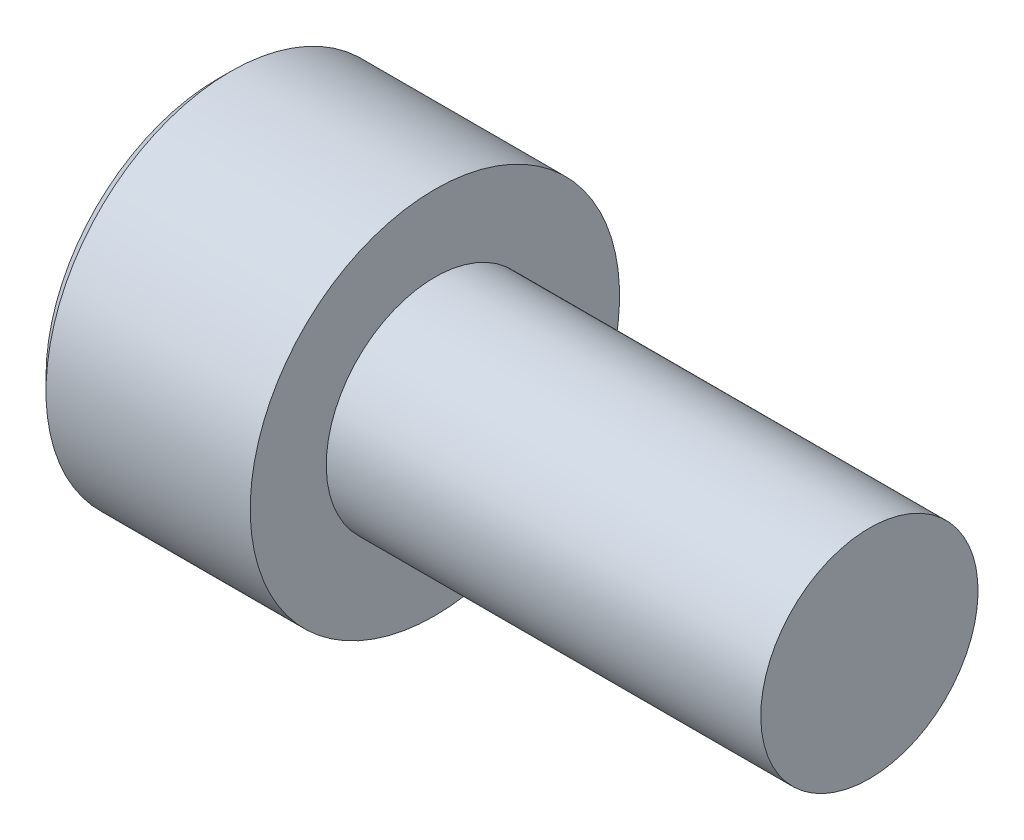
SolidWorks part; units mm, degrees
ref_plane "Front Plane" through (0, 0, 0) normal (0, 0, 1) x (1, 0, 0)
ref_plane "Top Plane" through (0, 0, 0) normal (0, 1, 0) x (1, 0, 0)
ref_plane "Right Plane" through (0, 0, 0) normal (1, 0, 0) x (0, 0, -1)
sketch "Sketch1" plane through (0, 0, 0) normal (0, 0, 1) x (1, 0, 0)
  line L0 (0, 2.5) -> (0, 4.25)
  line L1 (0, 4.25) -> (-5, 4.25)
  line L2 (-5, 4.25) -> (-5, 0)
  line L3 (-5, 0) -> (10, 0)
  line L4 (10, 0) -> (10, 2.5)
  line L5 (10, 2.5) -> (0, 2.5)
  line L6 (-5, 0) -> (10, 0) construction
  dimension "FIX_3" = 5
  dimension "FIX_4" = 8.5
  dimension "FIX_1" = 10
  dimension "FIX_2" = 5
revolve "Revolve1" add sketch "Sketch1" angle 360 about L6
cosmetic thread "Thread1" parameters "NFIX_1"=4.134
sketch "Sketch2" plane through (0, 0, 0) normal (0, 0, 1) x (1, 0, 0)
  line L0 (-5, 0) -> (-1.8453, 0)
  line L1 (-1.8453, 0) -> (-3, 2)
  line L2 (-3, 2) -> (-5, 2)
  line L3 (-5, 2) -> (-5, 0)
  line L4 (0, 0) -> (-5, 0) construction
  line L5 (-5, 0) -> (10, 0) construction
  dimension "FIX_8" = 4
  dimension "FIX_6" = 60
  dimension "FIX_7" = 2
revolve "Cut-Revolve1" cut sketch "Sketch2" angle 360 about L4
sketch "Sketch3" plane through (-5, 0, 0) normal (-1, 0, 0) x (0, 0, 1)
  line L1 (2.3094, 0) -> (1.1547, 2)
  line L2 (1.1547, 2) -> (-1.1547, 2)
  line L3 (-1.1547, 2) -> (-2.3094, 0)
  line L4 (-2.3094, 0) -> (-1.1547, -2)
  line L5 (-1.1547, -2) -> (1.1547, -2)
  line L6 (1.1547, -2) -> (2.3094, 0)
  circle A0 centre (0, 0) radius 2 construction
  dimension "FIX_10" = 4
extrude "Cut-Extrude1" cut sketch "Sketch3" against normal blind 2
chamfer "Chamfer1" distance 0.3 1 edges at (-5, -4.25, 0)
